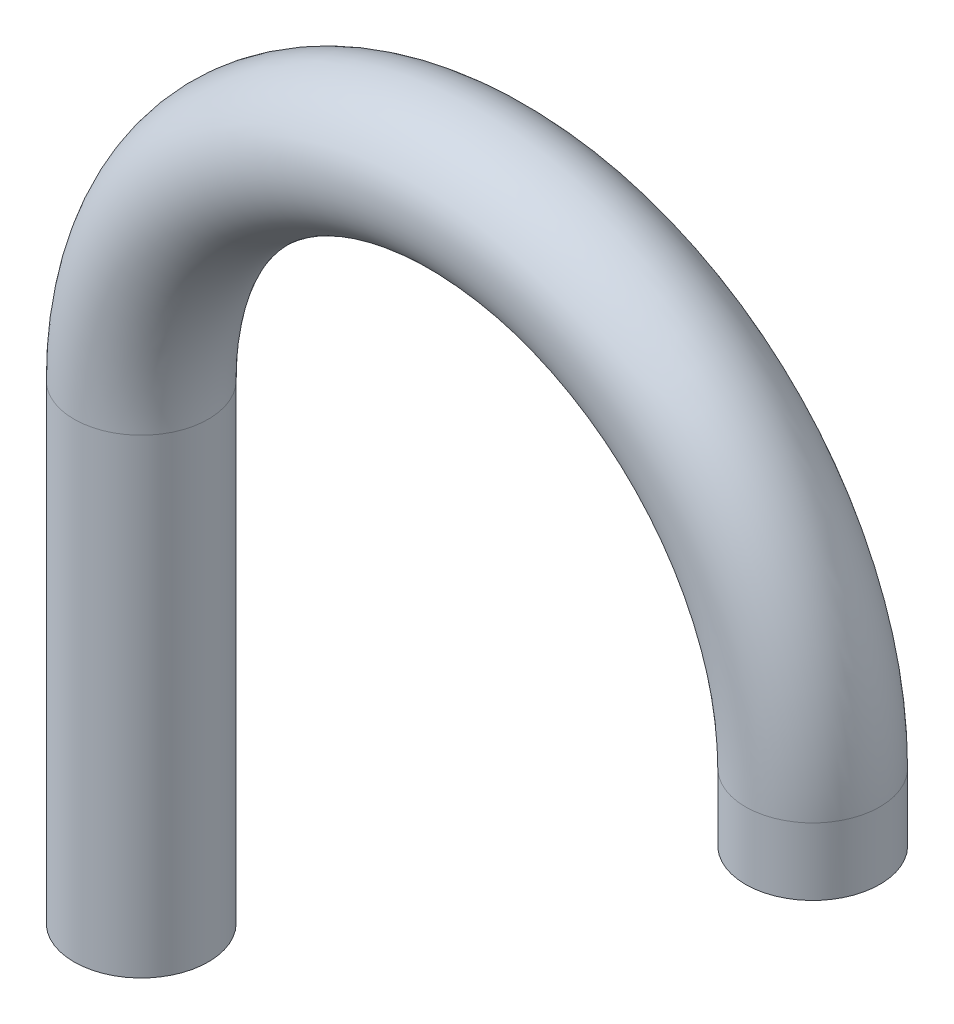
SolidWorks part; units mm, degrees
material "steel"
ref_plane "Przednia" through (0, 0, 0) normal (0, 0, 1) x (1, 0, 0)
ref_plane "Górna" through (0, 0, 0) normal (0, 1, 0) x (1, 0, 0)
ref_plane "Prawa" through (0, 0, 0) normal (1, 0, 0) x (0, 0, -1)
sketch "Sketch1" plane through (0, 0, 0) normal (0, 0, 1) x (1, 0, 0)
  line L0 (-5, 0) -> (-5, -7)
  line L2 (5, -1) -> (5, 0)
  arc A0 (5, 0) -> (-5, 0) centre (0, 0) ccw
  dimension "D1" = 5
  dimension "D2" = 7
  dimension "D3" = 1
ref_plane "Plane1" through (0, -7, 0) normal (0, 1, 0) x (1, 0, 0)
sketch "Sketch2" plane through (0, -7, 0) normal (0, 1, 0) x (1, 0, 0)
  circle A0 centre (-5, 0) radius 1
  dimension "D1" = 2
sweep "Sweep1" add profiles "Sketch2" path "Sketch1"
sketch "Sketch3" plane through (0, 0, 0) normal (0, 0, 1) x (1, 0, 0)
  line L0 (0, 0) -> (0, -4.6317) construction
sketch "Sketch4" plane through (0, 0, 0) normal (0, 0, 1) x (1, 0, 0)
  circle A0 centre (0.131, 1.2619) radius 2.75
  dimension "D1" = 5.5
